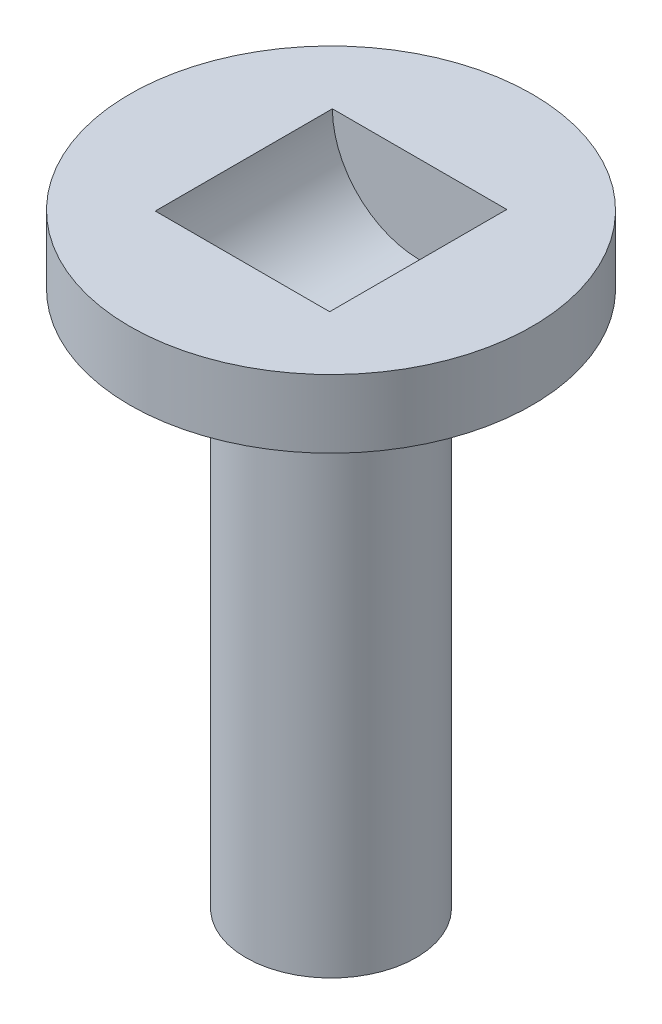
SolidWorks part; units mm, degrees
ref_plane "Front Plane" through (0, 0, 0) normal (0, 0, 1) x (1, 0, 0)
ref_plane "Top Plane" through (0, 0, 0) normal (0, 1, 0) x (1, 0, 0)
ref_plane "Right Plane" through (0, 0, 0) normal (1, 0, 0) x (0, 0, -1)
sketch "Sketch1" plane through (0, 0, 0) normal (0, 1, 0) x (1, 0, 0)
  circle A0 centre (0, 0) radius 3.175
  dimension "D1" = 6.35
extrude "Boss-Extrude1" add sketch "Sketch1" along normal blind 20
sketch "Sketch2" plane through (0, 0, 0) normal (0, -1, 0) x (1, 0, 0)
  circle A0 centre (0, 0) radius 0.9
  dimension "D1" = 1.8
extrude "Cut-Extrude1" cut sketch "Sketch2" against normal blind 10
sketch "Sketch4" plane through (0, 20, 0) normal (0, 1, 0) x (1, 0, 0)
  circle A0 centre (0, 0) radius 7.5
  dimension "D1" = 15
extrude "Boss-Extrude2" add sketch "Sketch4" along normal blind 2.54
sketch "Sketch6" plane through (0, 22.54, 0) normal (0, 1, 0) x (1, 0, 0)
  circle A0 centre (0, 0) radius 4.85
  dimension "D1" = 9.7
extrude "Boss-Extrude3" add sketch "Sketch6" against normal blind 3.35
sketch "Sketch5" plane through (0, 0, 0) normal (0, 0, 1) x (1, 0, 0)
  line L0 (7.5, 22.54) -> (-7.5, 22.54) construction
  circle A0 centre (0, 22.54) radius 3.25
  dimension "D1" = 6.5
extrude "Cut-Extrude3" cut sketch "Sketch5" against normal blind 3.302 and the other way blind 3.3
